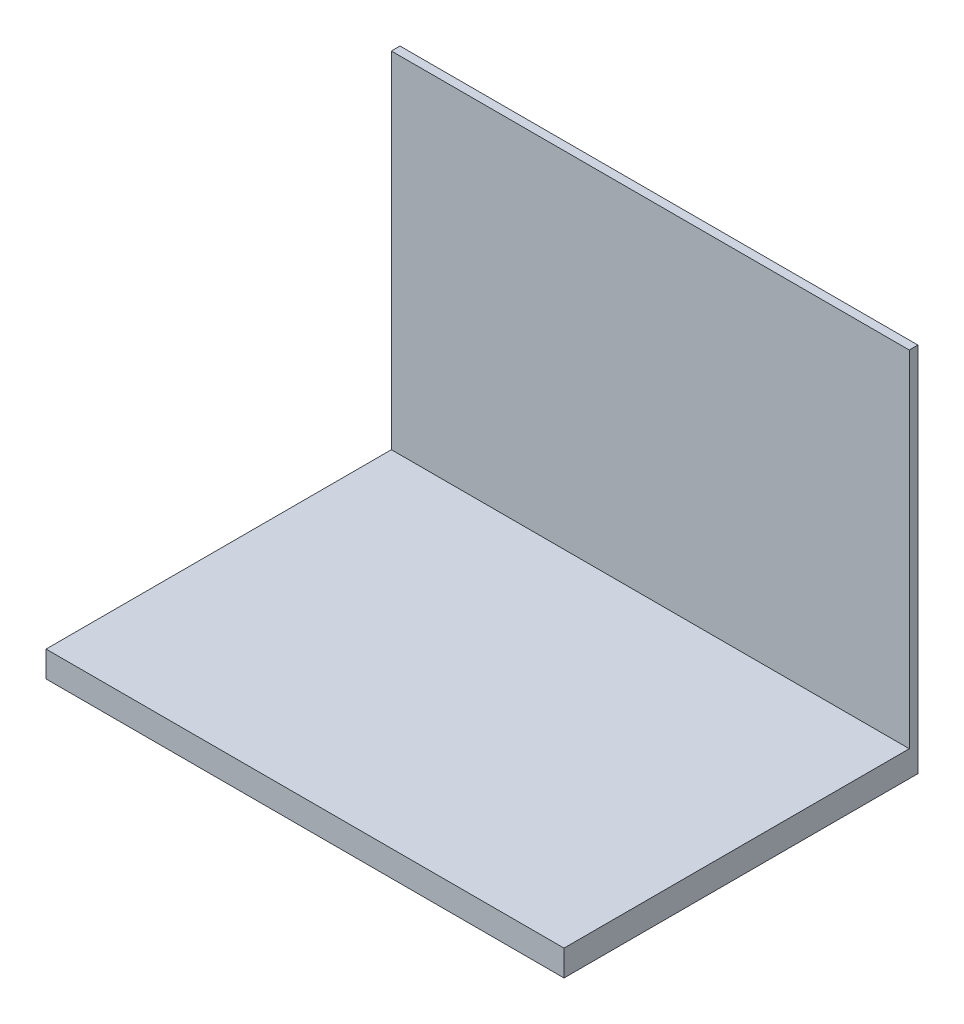
SolidWorks part; units mm, degrees
material "1060 Alloy"
ref_plane "Front Plane" through (0, 0, 0) normal (0, 0, 1) x (1, 0, 0)
ref_plane "Top Plane" through (0, 0, 0) normal (0, 1, 0) x (1, 0, 0)
ref_plane "Right Plane" through (0, 0, 0) normal (1, 0, 0) x (0, 0, -1)
sketch "Sketch1" plane through (0, 0, 0) normal (1, 0, 0) x (0, 0, -1)
  line L0 (0, 0) -> (0, 254)
  line L1 (0, 254) -> (6.35, 254)
  line L2 (6.35, 254) -> (6.35, -19.05)
  line L3 (6.35, -19.05) -> (-254, -19.05)
  line L4 (-254, -19.05) -> (-254, 0)
  line L5 (-254, 0) -> (0, 0)
  dimension "D1" = 90
  dimension "D2" = 254
  dimension "D3" = 19.05
  dimension "D4" = 6.35
extrude "Boss-Extrude1" add sketch "Sketch1" along normal mid plane 381
